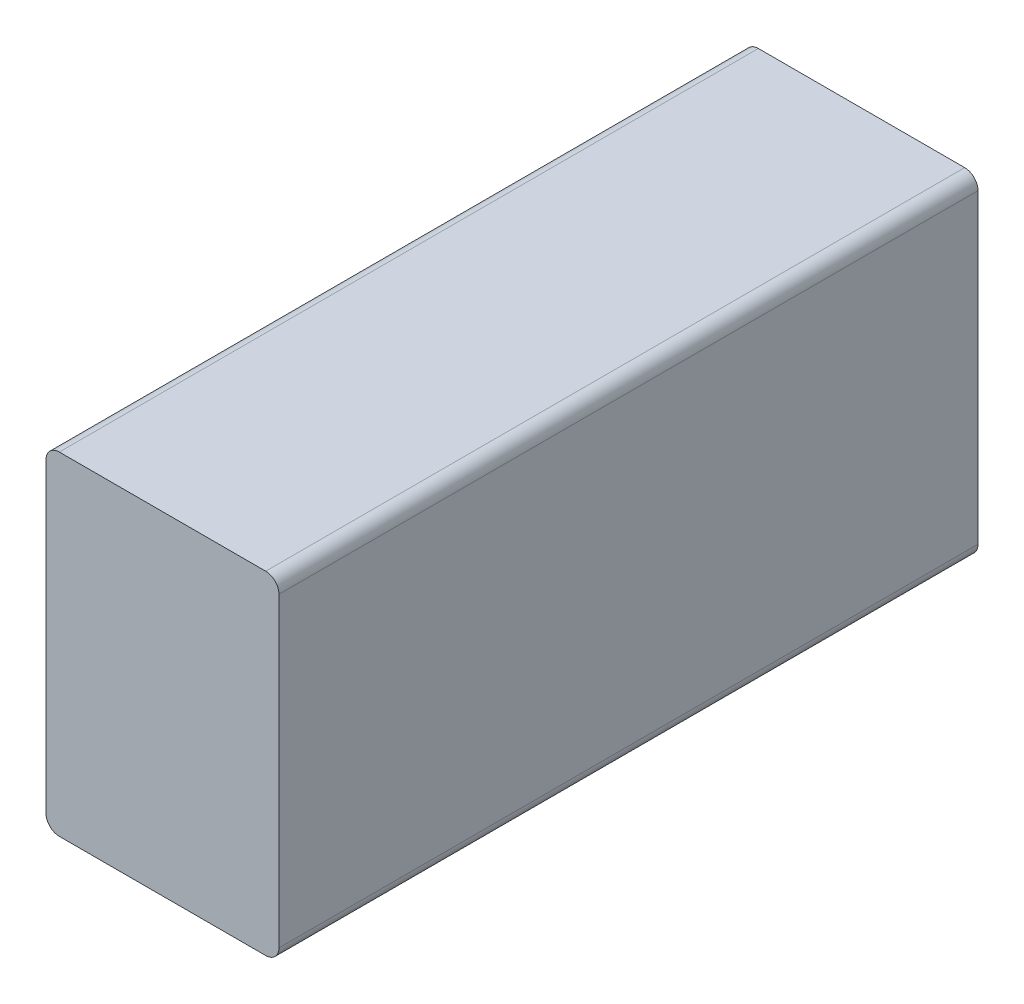
SolidWorks part; units mm, degrees
ref_plane "Front Plane" through (0, 0, 0) normal (0, 0, 1) x (1, 0, 0)
ref_plane "Top Plane" through (0, 0, 0) normal (0, 1, 0) x (1, 0, 0)
ref_plane "Right Plane" through (0, 0, 0) normal (1, 0, 0) x (0, 0, -1)
sketch "Sketch1" plane through (0, 0, 0) normal (0, 0, 1) x (1, 0, 0)
  line L1 (-17.5, -25) -> (17.5, -25)
  line L2 (-17.5, -25) -> (-17.5, 25)
  line L3 (-17.5, 25) -> (17.5, 25)
  line L4 (17.5, -25) -> (17.5, 25)
  line L5 (-17.5, -25) -> (17.5, 25) construction
  line L6 (-17.5, 25) -> (17.5, -25) construction
  point P0 (0, 0)
  dimension "D1" = 50
  dimension "D2" = 35
extrude "Boss-Extrude1" add sketch "Sketch1" along normal blind 105
fillet "Fillet1" radius 2 4 edges at (-17.5, -25, 52.5) (17.5, -25, 52.5) (-17.5, 25, 52.5) (17.5, 25, 52.5)
